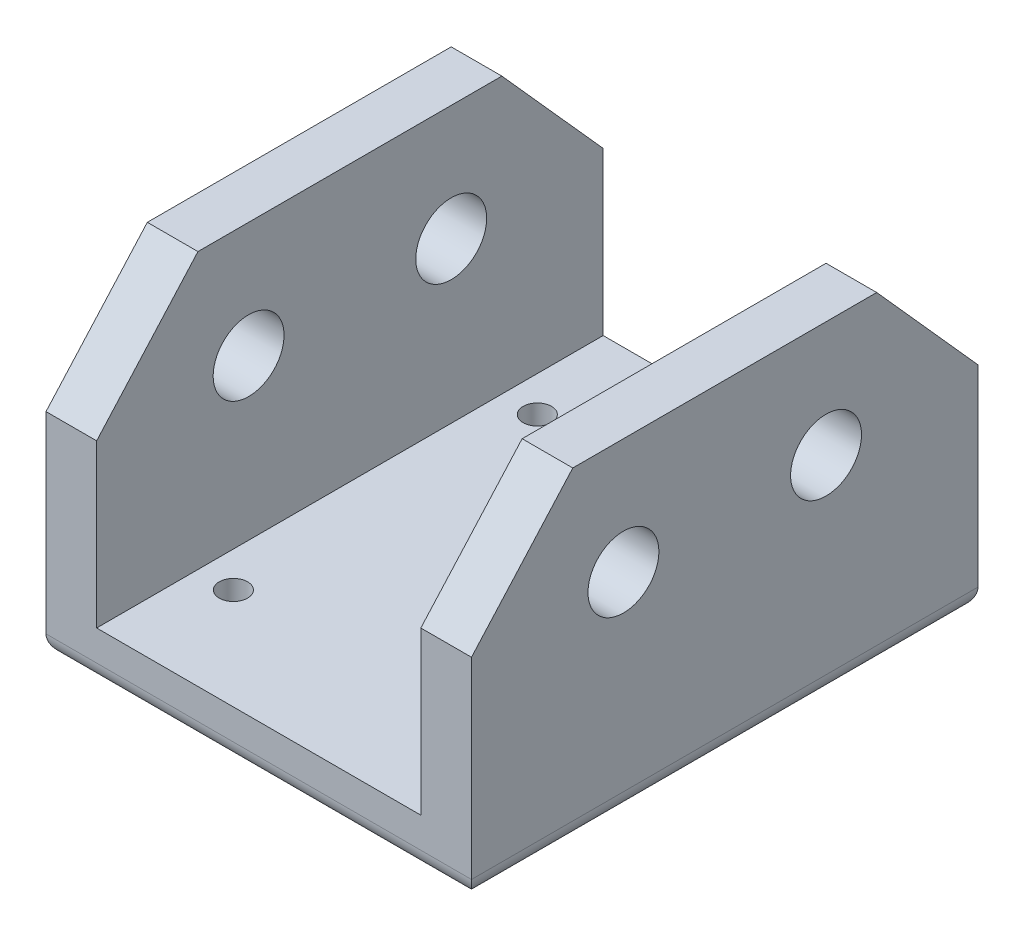
SolidWorks part; units mm, degrees
ref_plane "Front Plane" through (0, 0, 0) normal (0, 0, 1) x (1, 0, 0)
ref_plane "Top Plane" through (0, 0, 0) normal (0, 1, 0) x (1, 0, 0)
ref_plane "Right Plane" through (0, 0, 0) normal (1, 0, 0) x (0, 0, -1)
ref_plane "MiddlePlane" through (-26.67, 0, 0) normal (1, 0, 0) x (0, 0, -1)
sketch "Sketch1" plane through (0, 0, 0) normal (1, 0, 0) x (0, 0, -1)
  line L1 (0, 0) -> (63.5, 0)
  line L2 (0, 0) -> (0, 6.35)
  line L3 (0, 6.35) -> (63.5, 6.35)
  line L4 (63.5, 0) -> (63.5, 6.35)
  dimension "D1" = 6.35
  dimension "D2" = 63.5
extrude "Boss-Extrude1" add sketch "Sketch1" against normal blind 53.34
sketch "Sketch2" plane through (0, 0, 0) normal (1, 0, 0) x (0, 0, -1)
  line L0 (0, 6.35) -> (0, 26.67)
  line L1 (0, 26.67) -> (12.7, 40.869)
  line L2 (12.7, 40.869) -> (50.8, 40.869)
  line L3 (50.8, 40.869) -> (63.5, 26.67)
  line L4 (63.5, 26.67) -> (63.5, 6.35)
  line L5 (63.5, 6.35) -> (0, 6.35)
  point P7 (31.75, 40.869)
  point P10 (31.75, 6.35)
  dimension "D1" = 38.1
  dimension "D2" = 20.32
  dimension "D4" = 19.05
  dimension "D5" = 19.05
extrude "Boss-Extrude2" add sketch "Sketch2" against normal blind 6.35
sketch "Sketch11" plane through (0, 0, 0) normal (1, 0, 0) x (0, 0, -1)
  line L3 (50.8, 40.869) -> (12.7, 40.869) construction
  line L4 (0, 26.67) -> (0, 0) construction
  line L5 (63.5, 0) -> (63.5, 26.67) construction
  circle A4 centre (19.05, 26.391) radius 4.445
  circle A5 centre (44.45, 26.391) radius 4.445
  dimension "D1" = 8.89
  dimension "D3" = 19.05
  dimension "D4" = 19.05
  dimension "D2" = 14.478
extrude "Cut-Extrude1" cut sketch "Sketch11" against normal up to next
ref_plane "Plane2" through (0, 33.02, 0) normal (0, -1, 0) x (-1, 0, 0)
fillet "Fillet1" radius 2.54 4 edges at (0, 0, -31.75) (-53.34, 0, -31.75) (-26.67, 0, -63.5) (-26.67, 0, 0)
sketch "Sketch19" plane through (0, 0, 0) normal (0, -1, 0) x (1, 0, 0)
  line L0 (-26.67, -63.5) -> (-26.67, 0) construction
  line L1 (0, -63.5) -> (-53.34, -63.5) construction
  line L2 (-53.34, 0) -> (0, 0) construction
  line L3 (0, -31.75) -> (-53.34, -31.75) construction
  line L4 (0, 0) -> (0, -63.5) construction
  line L5 (-53.34, -63.5) -> (-53.34, 0) construction
  line L7 (-10.795, -50.8) -> (-42.545, -50.8) construction
  line L8 (-10.795, -50.8) -> (-10.795, -12.7) construction
  line L9 (-10.795, -12.7) -> (-42.545, -12.7) construction
  line L10 (-42.545, -50.8) -> (-42.545, -12.7) construction
  line L11 (-10.795, -50.8) -> (-42.545, -12.7) construction
  line L12 (-10.795, -12.7) -> (-42.545, -50.8) construction
  circle A0 centre (-10.795, -50.8) radius 1.778
  circle A1 centre (-42.545, -50.8) radius 1.778
  circle A2 centre (-42.545, -12.7) radius 1.778
  circle A3 centre (-10.795, -12.7) radius 1.778
  point P12 (-26.67, -31.75)
  dimension "D3" = 3.556
  dimension "D1" = 31.75
  dimension "D2" = 38.1
extrude "Cut-Extrude2" cut sketch "Sketch19" against normal up to next
mirror "Mirror1" about plane through (-26.67, 0, 0) normal (1, 0, 0) of "Cut-Extrude1", "Boss-Extrude2"
